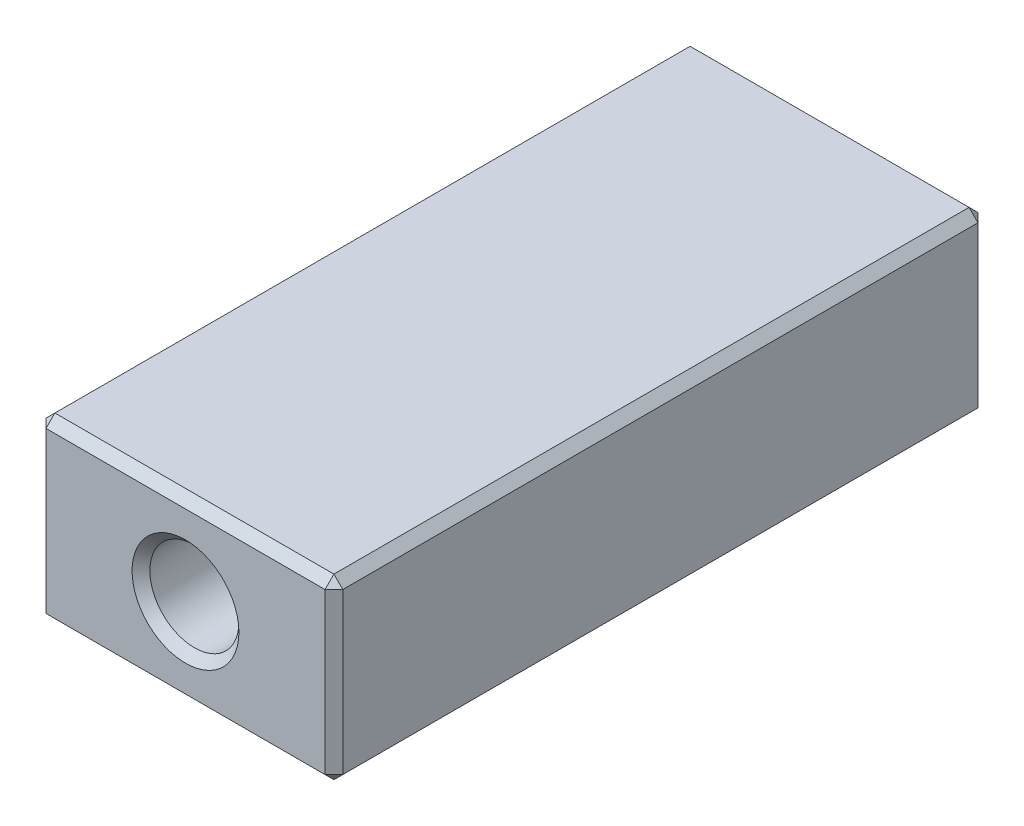
SolidWorks part; units mm, degrees
ref_plane "前视基准面" through (0, 0, 0) normal (0, 0, 1) x (1, 0, 0)
ref_plane "上视基准面" through (0, 0, 0) normal (0, 1, 0) x (1, 0, 0)
ref_plane "右视基准面" through (0, 0, 0) normal (1, 0, 0) x (0, 0, -1)
sketch "草图1" plane through (0, 0, 0) normal (0, 0, 1) x (1, 0, 0)
  line L1 (-5, 3) -> (5, 3)
  line L2 (-5, 3) -> (-5, -3)
  line L3 (-5, -3) -> (5, -3)
  line L4 (5, 3) -> (5, -3)
  line L5 (-5, 3) -> (5, -3) construction
  line L6 (-5, -3) -> (5, 3) construction
  point P0 (0, 0)
  dimension "D1" = 10
  dimension "D2" = 6
extrude "凸台-拉伸1" add sketch "草图1" along normal blind 22
sketch "草图2" [suppressed] plane through (-5, 0, 0) normal (-1, 0, 0) x (0, 0, 1)
  line L0 (0, 0) -> (22, 0) construction
  line L1 (22, 3) -> (22, -3) construction
  line L2 (11, -3) -> (11, 3) construction
  line L3 (22, -3) -> (0, -3) construction
  line L4 (22, 3) -> (0, 3) construction
  circle A0 centre (5, 0) radius 1.5
  circle A2 centre (17, 0) radius 1.5
  dimension "D1" = 3
  dimension "D2" = 6
sketch "草图3" plane through (0, 0, 0) normal (0, 0, -1) x (-1, 0, 0)
  circle A0 centre (0, 0) radius 1.5
  dimension "D1" = 3
extrude "切除-拉伸1" cut sketch "草图3" against normal through all
chamfer "倒角1" distance 0.3 angle 45 14 edges at (-1.5, 0, 22) (-1.5, 0, 0) (5, 0, 22) (0, -3, 22) (5, -3, 11) (-5, 0, 22) (-5, -3, 11) (-5, 0, 0) (0, -3, 0) (5, 0, 0) (5, 3, 11) (0, 3, 22) (-5, 3, 11) (0, 3, 0)
